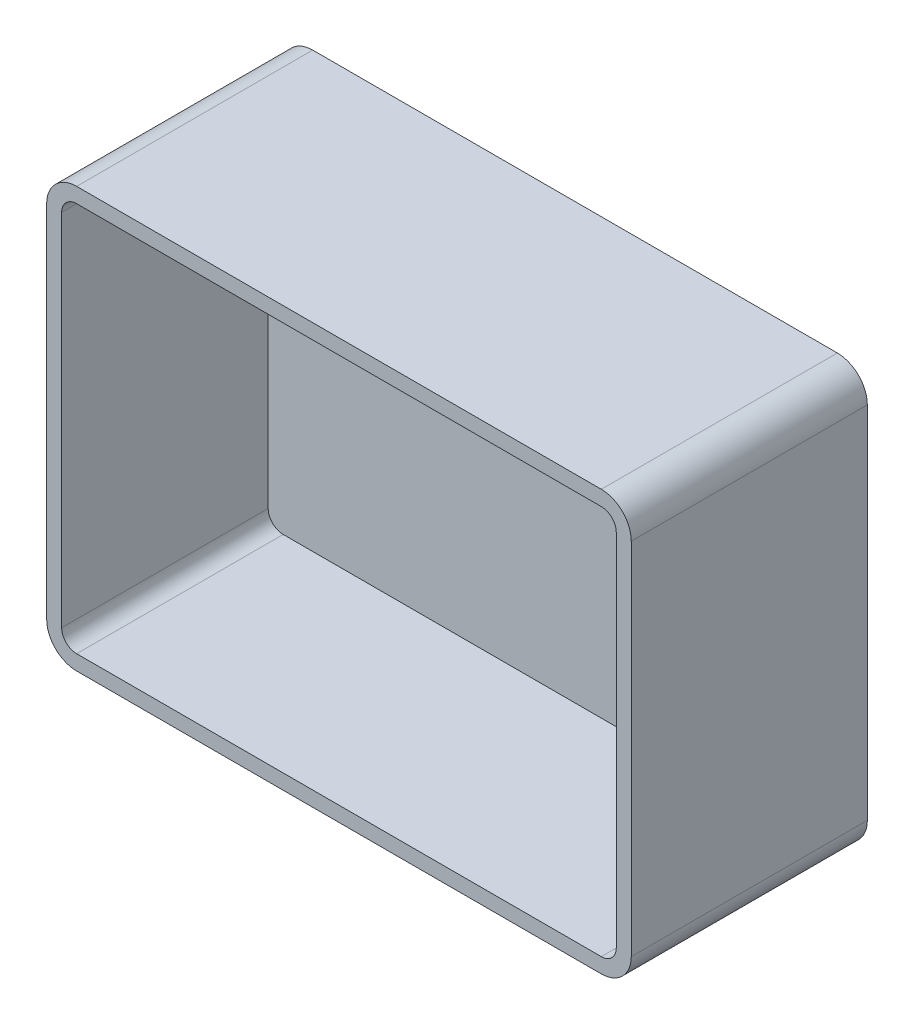
SolidWorks part; units mm, degrees
ref_plane "Front Plane" through (0, 0, 0) normal (0, 0, 1) x (1, 0, 0)
ref_plane "Top Plane" through (0, 0, 0) normal (0, 1, 0) x (1, 0, 0)
ref_plane "Right Plane" through (0, 0, 0) normal (1, 0, 0) x (0, 0, -1)
sketch "Sketch1" plane through (0, 0, 0) normal (0, 0, 1) x (1, 0, 0)
  line L1 (-48.9405, 35.4504) -> (50.1195, 35.4504)
  line L2 (-48.9405, 35.4504) -> (-48.9405, -35.6696)
  line L3 (-48.9405, -35.6696) -> (50.1195, -35.6696)
  line L4 (50.1195, 35.4504) -> (50.1195, -35.6696)
  dimension "D1" = 99.06
  dimension "D2" = 71.12
extrude "Boss-Extrude1" add sketch "Sketch1" along normal blind 40
fillet "Fillet1" radius 5.08 4 edges at (50.1195, 35.4504, 20) (-48.9405, 35.4504, 20) (-48.9405, -35.6696, 20) (50.1195, -35.6696, 20)
sketch "Sketch2" plane through (0, 0, 40) normal (0, 0, 1) x (1, 0, 0)
  line L8 (47.5795, -30.5896) -> (47.5795, 30.3704)
  line L9 (45.0395, 32.9104) -> (-43.8605, 32.9104)
  line L10 (-46.4005, 30.3704) -> (-46.4005, -30.5896)
  line L11 (-43.8605, -33.1296) -> (45.0395, -33.1296)
  line L12 (47.5795, -30.5896) -> (47.5795, 30.3704)
  line L13 (45.0395, 32.9104) -> (-43.8605, 32.9104)
  line L14 (-46.4005, 30.3704) -> (-46.4005, -30.5896)
  line L15 (-43.8605, -33.1296) -> (45.0395, -33.1296)
  arc A8 (47.5795, 30.3704) -> (45.0395, 32.9104) centre (45.0395, 30.3704) ccw
  arc A9 (-43.8605, 32.9104) -> (-46.4005, 30.3704) centre (-43.8605, 30.3704) ccw
  arc A10 (-46.4005, -30.5896) -> (-43.8605, -33.1296) centre (-43.8605, -30.5896) ccw
  arc A11 (45.0395, -33.1296) -> (47.5795, -30.5896) centre (45.0395, -30.5896) ccw
  arc A12 (47.5795, 30.3704) -> (45.0395, 32.9104) centre (45.0395, 30.3704) ccw
  arc A13 (-43.8605, 32.9104) -> (-46.4005, 30.3704) centre (-43.8605, 30.3704) ccw
  arc A14 (-46.4005, -30.5896) -> (-43.8605, -33.1296) centre (-43.8605, -30.5896) ccw
  arc A15 (45.0395, -33.1296) -> (47.5795, -30.5896) centre (45.0395, -30.5896) ccw
  dimension "D1" = 2.54
extrude "Cut-Extrude2" cut sketch "Sketch2" against normal blind 35
